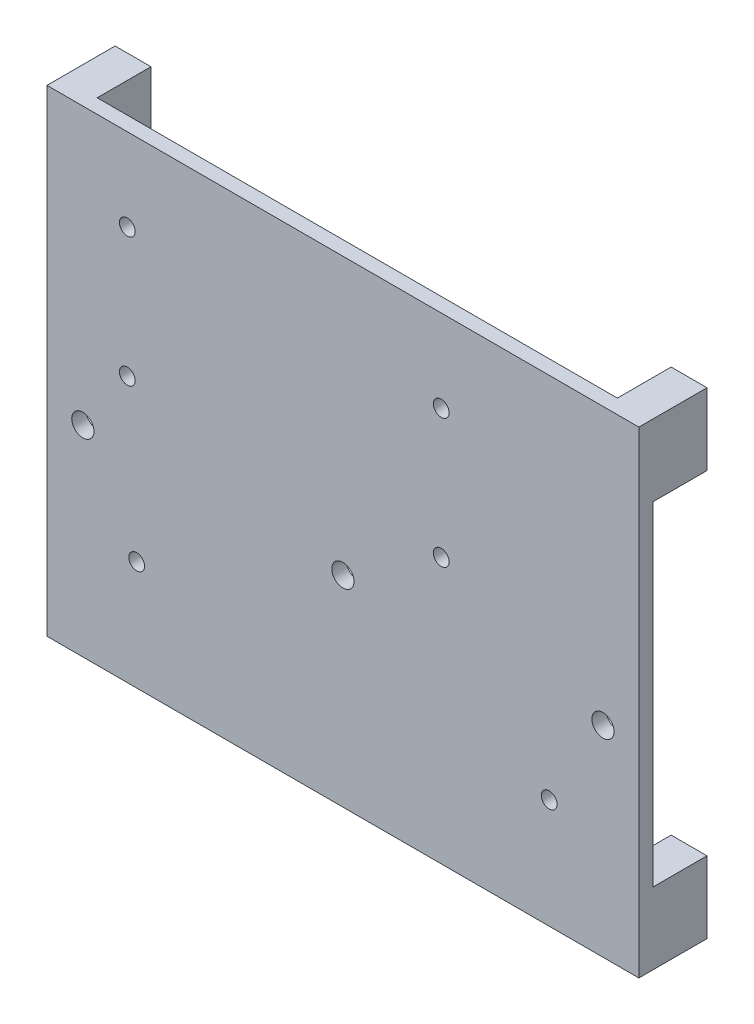
SolidWorks part; units mm, degrees
ref_plane "Front Plane" through (0, 0, 0) normal (0, 0, 1) x (1, 0, 0)
ref_plane "Top Plane" through (0, 0, 0) normal (0, 1, 0) x (1, 0, 0)
ref_plane "Right Plane" through (0, 0, 0) normal (1, 0, 0) x (0, 0, -1)
sketch "Sketch1" plane through (0, 0, 0) normal (0, 0, 1) x (1, 0, 0)
  line L8 (-62.5, 13.5) -> (-62.5, 5.25) construction
  line L9 (-82.5, -30.5) -> (82.5, -30.5)
  line L10 (-82.5, -30.5) -> (-82.5, 102.5)
  line L11 (-82.5, 102.5) -> (82.5, 102.5)
  line L12 (82.5, -30.5) -> (82.5, 102.5)
  line L13 (62.5, 5.25) -> (62.5, 13.5) construction
  line L14 (60.5, -15.5) -> (-60.5, -15.5) construction
  line L15 (-62.5, 87.5) -> (29.8, 87.5) construction
  dimension "D1" = 20
  dimension "D2" = 20
  dimension "D3" = 15
  dimension "D4" = 15
extrude "Boss-Extrude1" add sketch "Sketch1" along normal blind 4
sketch "Sketch2" plane through (0, 0, 0) normal (0, 0, -1) x (-1, 0, 0)
  circle A0 centre (-27.4, 43.5) radius 2.2
  circle A1 centre (60.1, 43.5) radius 2.2
  circle A2 centre (60.1, 79.5) radius 2.2
  circle A3 centre (-27.4, 79.5) radius 2.2
  circle A4 centre (57.5, 0) radius 2.2
  circle A5 centre (-57.5, 0) radius 2.2
  dimension "D1" = 4.4
  dimension "D2" = 4.4
  dimension "D3" = 4.4
  dimension "D4" = 4.4
  dimension "D5" = 4.4
  dimension "D6" = 4.4
extrude "Cut-Extrude1" cut sketch "Sketch2" against normal blind 4
sketch "Sketch3" plane through (0, 0, 0) normal (0, 0, -1) x (-1, 0, 0)
  line L1 (-82.5, -30.5) -> (-72.5, -30.5)
  line L2 (-82.5, -30.5) -> (-82.5, -10.5)
  line L3 (-82.5, -10.5) -> (-72.5, -10.5)
  line L4 (-72.5, -30.5) -> (-72.5, -10.5)
  line L5 (-82.5, 102.5) -> (-72.5, 102.5)
  line L6 (-82.5, 102.5) -> (-82.5, 82.5)
  line L7 (-82.5, 82.5) -> (-72.5, 82.5)
  line L8 (-72.5, 102.5) -> (-72.5, 82.5)
  line L9 (82.5, -30.5) -> (72.5, -30.5)
  line L10 (82.5, -30.5) -> (82.5, -10.5)
  line L11 (82.5, -10.5) -> (72.5, -10.5)
  line L12 (72.5, -30.5) -> (72.5, -10.5)
  line L13 (82.5, 102.5) -> (72.5, 102.5)
  line L14 (82.5, 102.5) -> (82.5, 82.5)
  line L15 (82.5, 82.5) -> (72.5, 82.5)
  line L16 (72.5, 102.5) -> (72.5, 82.5)
  dimension "D1" = 10
  dimension "D2" = 20
  dimension "D3" = 10
  dimension "D4" = 20
  dimension "D5" = 10
  dimension "D6" = 20
  dimension "D7" = 10
  dimension "D8" = 20
extrude "Boss-Extrude2" add sketch "Sketch3" along normal blind 15
sketch "Sketch4" plane through (0, 0, 0) normal (0, 0, -1) x (-1, 0, 0)
  line L0 (-82.5, -10.5) -> (-82.5, 82.5) construction
  line L1 (82.5, 82.5) -> (82.5, -10.5) construction
  line L2 (-82.5, 25.5) -> (82.5, 25.5) construction
  line L3 (60.5, 15.5) -> (-60.5, 15.5) construction
  circle A0 centre (-72.5, 25.5) radius 3.1
  circle A1 centre (72.5, 25.5) radius 3.1
  circle A2 centre (0, 25.5) radius 3.1
  circle A3 centre (0, 25.5) radius 4.25 construction
  dimension "D1" = 6.2
  dimension "D2" = 6.2
  dimension "D3" = 6.2
  dimension "D6" = 8.5
  dimension "D4" = 10
  dimension "D5" = 10
  dimension "D7" = 10
extrude "Cut-Extrude2" cut sketch "Sketch4" against normal up to next
